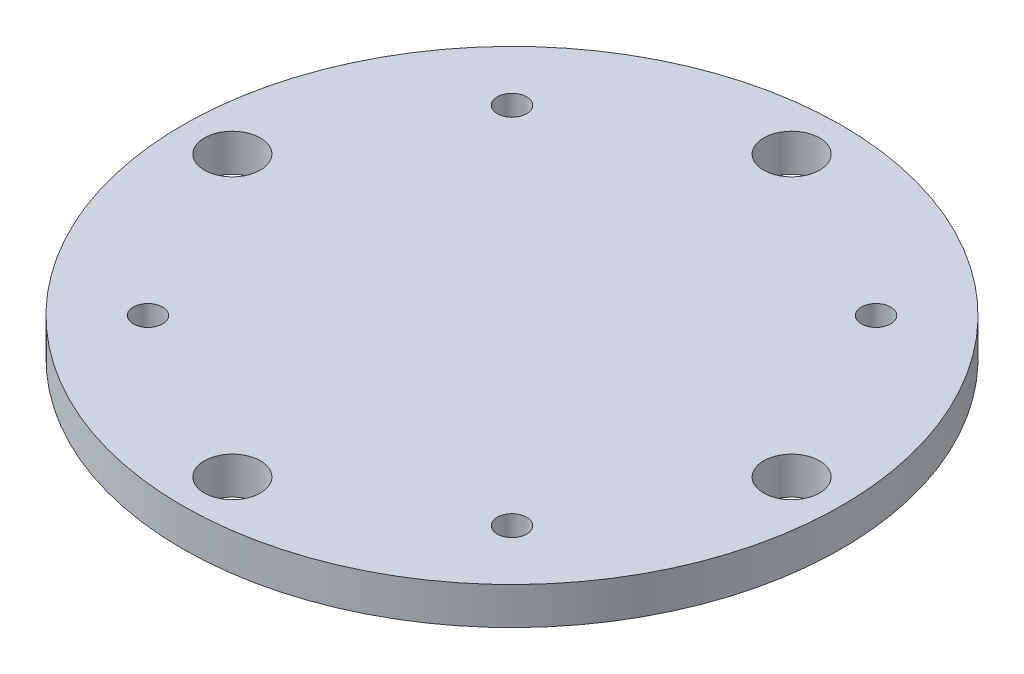
SolidWorks part; units mm, degrees
material "Delrin 2700 NC010, Low Viscosity Acetal Copolymer (SS)"
ref_plane "Front Plane" through (0, 0, 0) normal (0, 0, 1) x (1, 0, 0)
ref_plane "Top Plane" through (0, 0, 0) normal (0, 1, 0) x (1, 0, 0)
ref_plane "Right Plane" through (0, 0, 0) normal (1, 0, 0) x (0, 0, -1)
sketch "Sketch1" plane through (0, 0, 0) normal (0, 1, 0) x (1, 0, 0)
  line L1 (19.8438, -19.8437) -> (-19.8437, -19.8438) construction
  line L2 (19.8438, -19.8437) -> (19.8438, 19.8438) construction
  line L3 (19.8438, 19.8438) -> (-19.8437, 19.8438) construction
  line L4 (-19.8437, -19.8438) -> (-19.8437, 19.8438) construction
  line L5 (19.8438, -19.8437) -> (-19.8437, 19.8438) construction
  line L6 (19.8438, 19.8438) -> (-19.8437, -19.8438) construction
  circle A0 centre (0, 0) radius 28.0633
  point P0 (0, 0)
  dimension "Stepper Width" = 39.6875
extrude "Boss-Extrude1" add sketch "Sketch1" along normal blind 3.175
hole_wizard "M3x0.5 Tapped Hole1" positions "Sketch4" profile "Sketch3" tap size "M3x0.5" standard "ANSI Metric"
sketch "Sketch4" plane through (0, 3.175, 0) normal (0, 1, 0) x (1, 0, 0)
  line L1 (15.5, -15.5) -> (-15.5, -15.5) construction
  line L2 (15.5, -15.5) -> (15.5, 15.5) construction
  line L3 (15.5, 15.5) -> (-15.5, 15.5) construction
  line L4 (-15.5, -15.5) -> (-15.5, 15.5) construction
  line L5 (15.5, -15.5) -> (-15.5, 15.5) construction
  line L6 (15.5, 15.5) -> (-15.5, -15.5) construction
  point P2 (-15.5, 15.5)
  point P51 (15.5, -15.5)
  point P52 (15.5, 15.5)
  point P53 (-15.5, -15.5)
  dimension "Stepper Hole Spacing" = 31
sketch "Sketch3" plane through (-15.5, 3.175, -15.5) normal (1, 0, 0) x (0, 0, 1)
  line L0 (0, 0) -> (0, 8.3711)
  line L1 (0, 8.3711) -> (1.25, 7.62)
  line L2 (1.25, 7.62) -> (1.25, 0)
  line L5 (1.25, 0) -> (0, 0)
  line L10 (0, 8.3711) -> (-1.25, 7.62) construction
  line L11 (0, -6.35) -> (0, 107.95) construction
  dimension "Tap Drill Dia." = 2.5
  dimension "Tap Drill Depth" = 7.62
  dimension "Drill Angle" = 118
sketch "Sketch5" plane through (0, 3.175, 0) normal (0, 1, 0) x (1, 0, 0)
  line L0 (0, 28.0633) -> (0, -28.0633) construction
  circle A0 centre (0, 0) radius 28.0633 construction
  circle A1 centre (0, 0) radius 23.8125 construction
  circle A2 centre (0, 23.8125) radius 2.3813
  dimension "D1" = 47.625
  dimension "D2" = 4.7625
extrude "Cut-Extrude1" cut sketch "Sketch5" against normal through all
pattern_circular "CirPattern1" count 4 over 360 about axis through (0, 0, 0) along (0, 1, 0) of "Cut-Extrude1"
